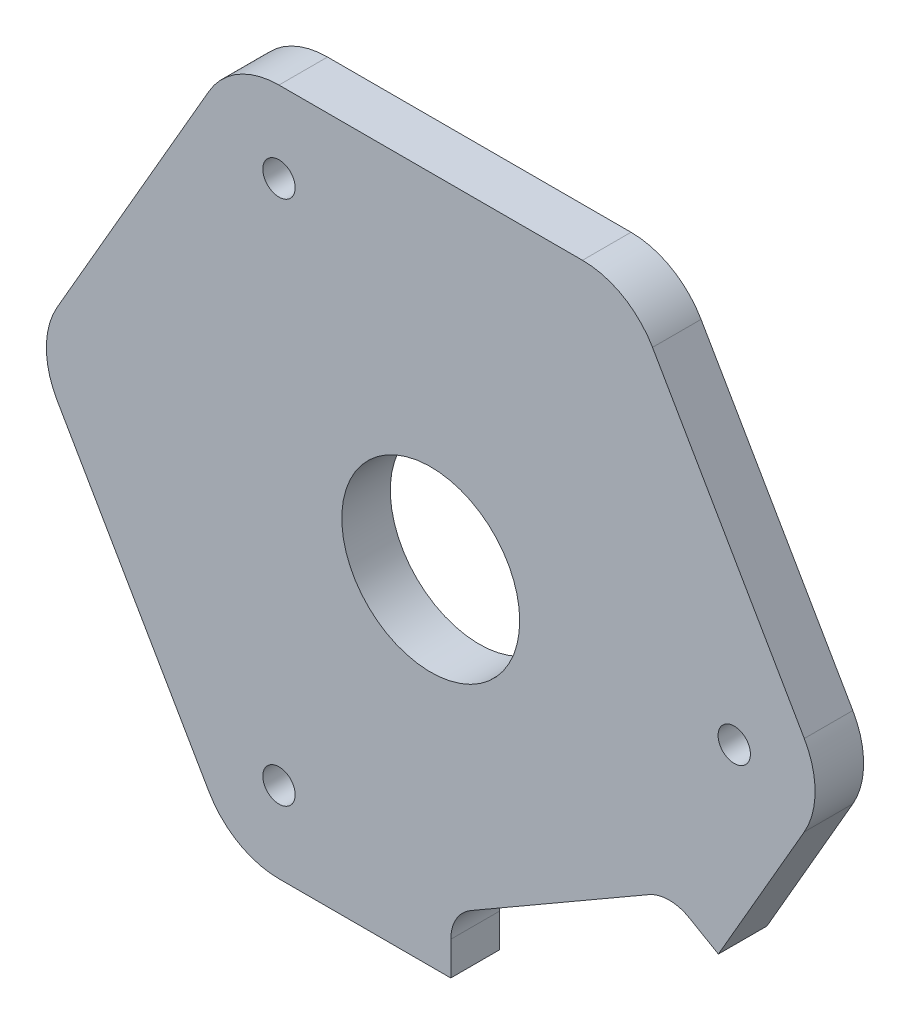
SolidWorks part; units mm, degrees
ref_plane "Front Plane" through (0, 0, 0) normal (0, 0, 1) x (1, 0, 0)
ref_plane "Top Plane" through (0, 0, 0) normal (0, 1, 0) x (1, 0, 0)
ref_plane "Right Plane" through (0, 0, 0) normal (1, 0, 0) x (0, 0, -1)
sketch "Sketch1" plane through (0, 0, 0) normal (0, 0, 1) x (1, 0, 0)
  line L9 (-95.2285, 77.3455) -> (-73.9877, 77.3455)
  line L10 (-73.9877, 81.4917) -> (-73.9877, 77.3455)
  line L11 (-49.4877, 98.5235) -> (-71.4877, 85.8218)
  line L12 (-40.897, 96.4504) -> (-44.4877, 98.5235)
  line L13 (-40.897, 96.4504) -> (-30.2766, 114.8455)
  line L14 (-30.2766, 124.8455) -> (-49.0405, 157.3455)
  line L15 (-57.7007, 162.3455) -> (-95.2285, 162.3455)
  line L16 (-103.8888, 157.3455) -> (-122.6526, 124.8455)
  line L17 (-122.6526, 114.8455) -> (-103.8888, 82.3455)
  circle A11 centre (-38.9369, 119.8455) radius 2
  circle A12 centre (-95.2285, 152.3455) radius 2
  circle A13 centre (-76.4646, 119.8455) radius 11
  circle A14 centre (-95.2285, 87.3455) radius 2
  arc A15 (-103.8888, 82.3455) -> (-95.2285, 77.3455) centre (-95.2285, 87.3455) ccw
  arc A16 (-71.4877, 85.8218) -> (-73.9877, 81.4917) centre (-68.9877, 81.4917) ccw
  arc A17 (-44.4877, 98.5235) -> (-49.4877, 98.5235) centre (-46.9877, 94.1934) ccw
  arc A18 (-30.2766, 114.8455) -> (-30.2766, 124.8455) centre (-38.9369, 119.8455) ccw
  arc A19 (-49.0405, 157.3455) -> (-57.7007, 162.3455) centre (-57.7007, 152.3455) ccw
  arc A20 (-95.2285, 162.3455) -> (-103.8888, 157.3455) centre (-95.2285, 152.3455) ccw
  arc A21 (-122.6526, 124.8455) -> (-122.6526, 114.8455) centre (-113.9924, 119.8455) ccw
  point P1 (0, 0)
  dimension "D9" = 10
  dimension "D20" = 5
  dimension "D26" = 22
  dimension "D29" = 4
  dimension "D1" = 37.5278
  dimension "D2" = 96.4504
  dimension "D3" = 40.897
  dimension "D4" = 110.0677
  dimension "D5" = 25.4034
  dimension "D6" = 21.2408
  dimension "D7" = 90
  dimension "D8" = 90
  dimension "D10" = 10
  dimension "D11" = 10
  dimension "D12" = 60
  dimension "D13" = 60
  dimension "D14" = 60
  dimension "D15" = 60
  dimension "D16" = 60
  dimension "D17" = 65
  dimension "D18" = 65
  dimension "D19" = 65
  dimension "D21" = 60
  dimension "D22" = 60
  dimension "D23" = 4.1462
  dimension "D24" = 4.1462
  dimension "D25" = 77.3455
  dimension "D27" = 37.5278
  dimension "D28" = 37.5278
extrude "Boss-Extrude1" add sketch "Sketch1" along normal blind 6 separate body
